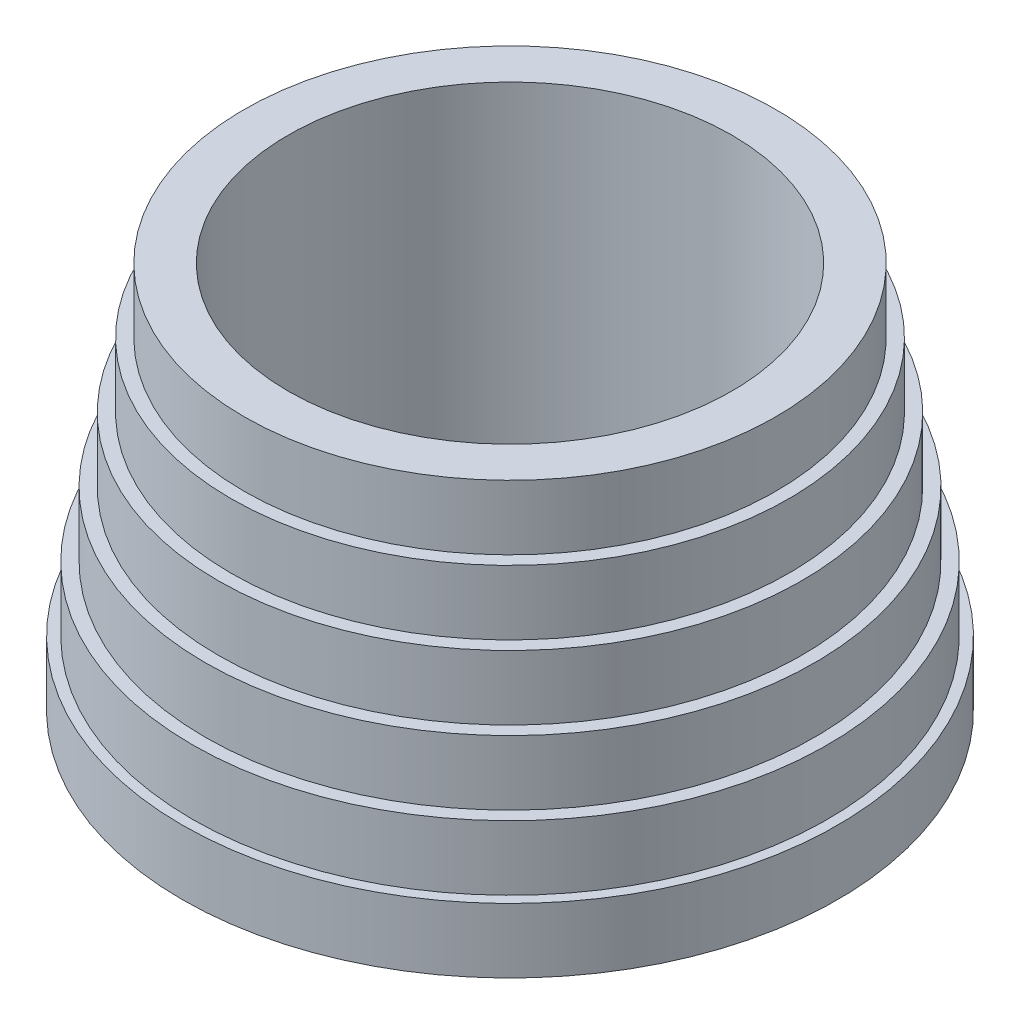
SolidWorks part; units mm, degrees
ref_plane "Front Plane" through (0, 0, 0) normal (0, 0, 1) x (1, 0, 0)
ref_plane "Top Plane" through (0, 0, 0) normal (0, 1, 0) x (1, 0, 0)
ref_plane "Right Plane" through (0, 0, 0) normal (1, 0, 0) x (0, 0, -1)
sketch "Sketch4" plane through (0, 0, 0) normal (0, 0, 1) x (1, 0, 0)
  line L0 (0, 105.4944) -> (0, -194.5056) construction
  line L1 (-253.7753, -190) -> (-245.9942, -190)
  line L2 (-253.7753, -190) -> (-253.7753, -140)
  line L3 (-253.7753, -140) -> (-245.9942, -140)
  line L4 (-245.9942, -140) -> (-245.9942, -90)
  line L5 (-245.9942, -90) -> (-235.9942, -90)
  line L6 (-235.9942, -90) -> (-235.9942, -40)
  line L7 (-235.9942, -40) -> (-225.9942, -40)
  line L8 (-225.9942, -40) -> (-225.9942, 10)
  line L9 (-225.9942, 10) -> (-215.9942, 10)
  line L10 (-215.9942, 10) -> (-215.9942, 60)
  line L11 (-215.9942, 60) -> (-205.9942, 60)
  line L12 (-205.9942, 60) -> (-205.9942, 110)
  line L13 (-205.9942, 110) -> (-195.9942, 110)
  line L14 (-195.9942, 110) -> (-195.9942, 50)
  line L15 (-245.9942, -190) -> (-245.9942, -150)
  line L16 (-245.9942, -150) -> (-235.9942, -150)
  line L17 (-235.9942, -150) -> (-235.9942, -100)
  line L18 (-235.9942, -100) -> (-225.9942, -100)
  line L19 (-225.9942, -100) -> (-225.9942, -50)
  line L20 (-225.9942, -50) -> (-215.9942, -50)
  line L21 (-215.9942, -50) -> (-215.9942, 0)
  line L22 (-215.9942, 0) -> (-205.9942, 0)
  line L23 (-205.9942, 0) -> (-205.9942, 50)
  line L24 (-205.9942, 50) -> (-195.9942, 50)
  dimension "D1" = 300
  dimension "D2" = 7.7811
  dimension "D3" = 50
  dimension "D4" = 50
  dimension "D5" = 10
  dimension "D6" = 50
  dimension "D7" = 10
  dimension "D8" = 50
  dimension "D9" = 10
  dimension "D10" = 50
  dimension "D11" = 10
  dimension "D12" = 50
  dimension "D13" = 10
  dimension "D14" = 60
  dimension "D15" = 10
  dimension "D16" = 50
  dimension "D17" = 10
  dimension "D18" = 50
  dimension "D19" = 10
  dimension "D20" = 50
  dimension "D21" = 10
  dimension "D22" = 50
  dimension "D23" = 10
revolve "Revolve3" add sketch "Sketch4" angle 360 about L0
sketch "Sketch8" plane through (0, 0, 0) normal (1, 0, 0) x (0, 0, -1)
  line L0 (0, 0) -> (0, 164.3638) construction
  line L1 (205.9942, 110) -> (215.9942, 110)
  line L2 (215.9942, 110) -> (215.9942, 140)
  line L3 (215.9942, 140) -> (205.9942, 140)
  line L4 (205.9942, 140) -> (205.9942, 110)
  dimension "D1" = 10
  dimension "D2" = 30
sketch "Sketch9" plane through (0, 110, 0) normal (0, 1, 0) x (1, 0, 0)
  circle A0 centre (0, 0) radius 195.9942
  circle A1 centre (0, 0) radius 171.7791
extrude "Boss-Extrude1" add sketch "Sketch9" against normal blind 280.9855
chamfer "Chamfer1" distance 10 angle 45 1 edges at (0, -170.9855, 195.9942)
